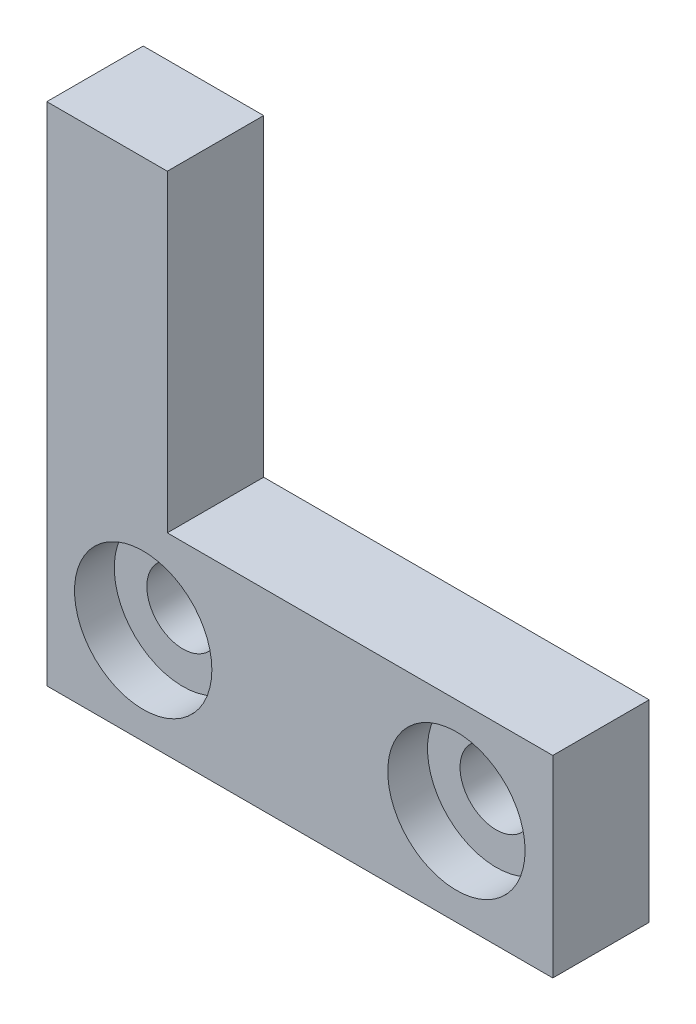
SolidWorks part; units mm, degrees
ref_plane "Alzado" through (0, 0, 0) normal (0, 0, 1) x (1, 0, 0)
ref_plane "Planta" through (0, 0, 0) normal (0, 1, 0) x (1, 0, 0)
ref_plane "Vista lateral" through (0, 0, 0) normal (1, 0, 0) x (0, 0, -1)
sketch "Croquis1" plane through (0, 0, 0) normal (0, 0, 1) x (1, 0, 0)
  line L1 (5, -75) -> (18, -75)
  line L2 (5, -75) -> (5, -83) construction
  line L3 (5, -83) -> (18, -83)
  line L4 (18, -75) -> (18, -83)
  line L5 (5, -75) -> (18, -83) construction
  line L6 (5, -83) -> (18, -75) construction
  line L8 (5, -83) -> (-3, -83)
  line L9 (5, -83) -> (5, -62)
  line L10 (5, -62) -> (-3, -62)
  line L11 (-3, -83) -> (-3, -62)
  line L12 (5, -83) -> (-3, -62) construction
  line L13 (5, -62) -> (-3, -83) construction
  circle A0 centre (14, -79) radius 1.5
  circle A1 centre (1, -79) radius 1.5
  point P4 (11.5, -79)
  point P11 (1, -72.5)
  dimension "D2" = 21
  dimension "D4" = 3
  dimension "D5" = 8
  dimension "D1" = 8
  dimension "D3" = 4
  dimension "D6" = 21
  dimension "D7" = 4
  dimension "D10" = 4
extrude "Saliente-Extruir1" add sketch "Croquis1" along normal blind 4
sketch "Croquis2" plane through (0, 0, 4) normal (0, 0, 1) x (1, 0, 0)
  circle A0 centre (1, -79) radius 2.85
  circle A2 centre (14, -79) radius 2.85
extrude "Cortar-Extruir1" cut sketch "Croquis2" against normal blind 1.65
sketch "Croquis3" plane through (0, -62, 0) normal (0, 1, 0) x (1, 0, 0)
  line L0 (5, 0) -> (-3, 0) construction
  line L1 (5, -4) -> (2, -4)
  line L2 (5, -4) -> (5, 0)
  line L3 (5, 0) -> (2, 0)
  line L4 (2, -4) -> (2, 0)
  line L5 (5, -4) -> (2, 0) construction
  line L6 (5, 0) -> (2, -4) construction
  point P4 (3.5, -2)
  dimension "D1" = 3
extrude "Cortar-Extruir2" cut sketch "Croquis3" against normal up to surface (13 mm away) up to face at (11.5, -75, 2)
